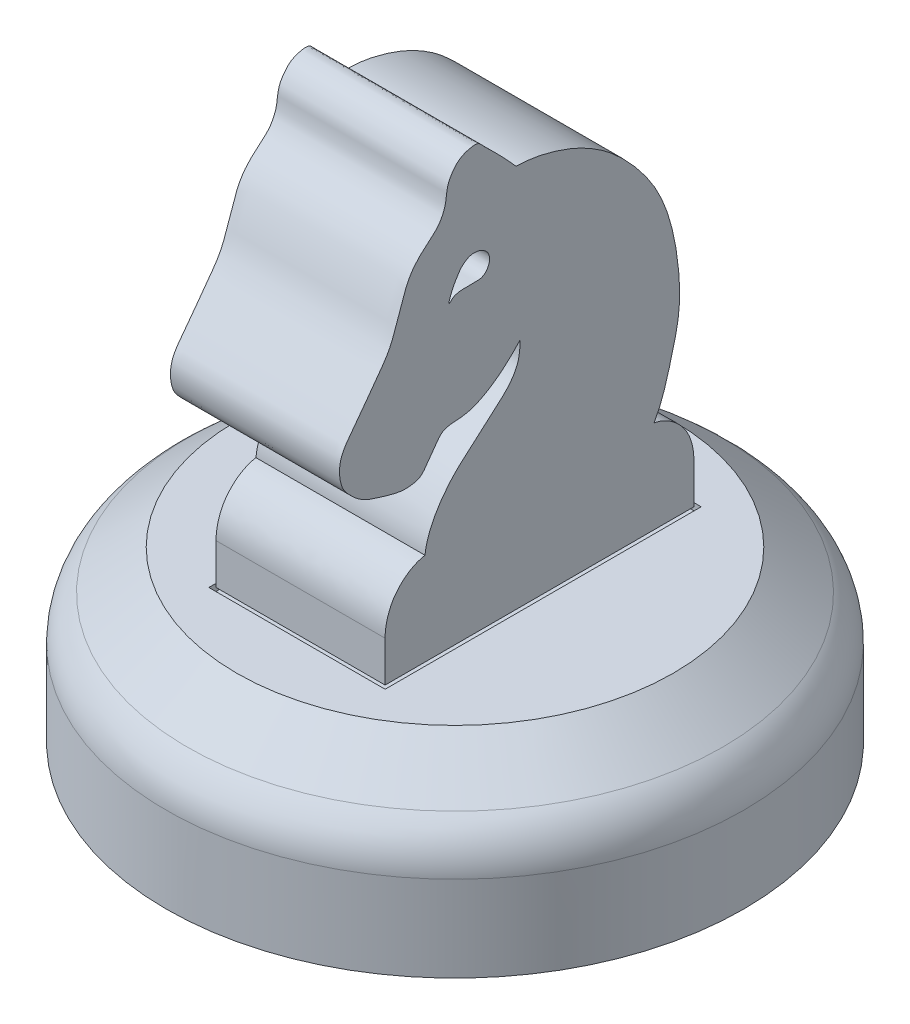
SolidWorks part; units mm, degrees
ref_plane "Front" through (0, 0, 0) normal (0, 0, 1) x (1, 0, 0)
ref_plane "Top" through (0, 0, 0) normal (0, 1, 0) x (1, 0, 0)
ref_plane "Right" through (0, 0, 0) normal (1, 0, 0) x (0, 0, -1)
sketch "Sketch1" plane through (0, 0, 0) normal (0, 1, 0) x (1, 0, 0)
  circle A0 centre (0, 0) radius 16.2719
  dimension "D1" = 32.5437
extrude "Boss-Extrude1" add sketch "Sketch1" along normal blind 6.35
sketch "Sketch2" plane through (0, 0, 0) normal (0, 0, 1) x (1, 0, 0)
  line L0 (-16.2719, 6.35) -> (-12.3031, 9.525)
  line L1 (-12.3031, 9.525) -> (0, 9.525)
  line L2 (0, 9.525) -> (0, 6.35)
  line L3 (16.2719, 6.35) -> (-16.2719, 6.35) construction
  line L4 (0, 6.35) -> (-16.2719, 6.35)
  line L5 (-16.2719, 0) -> (16.2719, 0) construction
  dimension "D1" = 3.9688
  dimension "D2" = 9.525
revolve "Revolve1" add sketch "Sketch2" angle 360 about L2
fillet "Fillet1" radius 3.175 1 edges at (0, 6.35, 16.2719)
sketch "Sketch3" plane through (0, 0, 0) normal (0, -1, 0) x (1, 0, 0)
  line L1 (-6.4516, -9.6266) -> (6.4516, -9.6266)
  line L2 (-6.4516, -9.6266) -> (-6.4516, 9.6266)
  line L3 (-6.4516, 9.6266) -> (6.4516, 9.6266)
  line L4 (6.4516, -9.6266) -> (6.4516, 9.6266)
  line L5 (-6.4516, -9.6266) -> (6.4516, 9.6266) construction
  line L6 (-6.4516, 9.6266) -> (6.4516, -9.6266) construction
  point P0 (0, 0)
  dimension "D1" = 19.2532
  dimension "D2" = 12.9032
extrude "Cut-Extrude1" cut sketch "Sketch3" against normal blind 4.7625
hole_wizard "#6 (0.204) Diameter Hole1" positions "Sketch4" profile "Sketch5" hole size "#6" standard "ANSI Inch" end condition through all
sketch "Sketch4" plane through (0, 4.7625, 0) normal (0, -1, 0) x (-1, 0, 0)
  point P0 (0, 0)
sketch "Sketch5" plane through (0, 4.7625, 0) normal (1, 0, 0) x (0, 0, -1)
  line L0 (0, 0) -> (0, 4.7625)
  line L1 (0, 4.7625) -> (2.5908, 4.7625)
  line L2 (2.5908, 4.7625) -> (2.5908, 0)
  line L5 (2.5908, 0) -> (0, 0)
  line L11 (0, -6.35) -> (0, 107.95) construction
  dimension "Thru Hole Dia." = 5.1816
  dimension "Thru Hole Depth" = 4.7625
sketch "Sketch6" plane through (0, 0, 0) normal (1, 0, 0) x (0, 0, -1)
  line L0 (27.0775, 134.8707) -> (197.7441, 134.8707) construction
  line L1 (-8.6995, 9.525) -> (8.6995, 9.525)
  line L2 (12.3031, 9.525) -> (-12.3031, 9.525) construction
  line L3 (-8.6995, 9.525) -> (-8.6995, 11.811)
  line L4 (8.6995, 9.525) -> (8.6995, 11.811)
  line L5 (0, 50) -> (0, -50) construction
  spline S0 degree 3 poles (-8.6995, 11.811) (-8.6995, 11.9816) (-8.6727, 12.3664) (-8.5285, 12.9065) (-8.2839, 13.452) (-7.7049, 14.2088) (-7.0216, 14.6403) (-6.4552, 14.738) knots 0 0 0 0 0.128234 0.288855 0.417857 0.575529 1 1 1 1
  spline S1 degree 3 poles (8.6995, 11.811) (8.6995, 11.9816) (8.6727, 12.3664) (8.5285, 12.9065) (8.2839, 13.452) (7.7049, 14.2088) (7.0216, 14.6403) (6.4552, 14.738) knots 0 0 0 0 0.128234 0.288855 0.417857 0.575529 1 1 1 1
  spline S2 degree 3 poles (-6.4552, 14.738) (-6.3837, 15.3671) (-5.8874, 16.6148) (-4.8428, 17.8972) (-3.6608, 18.894) (-2.7793, 19.6924) (-1.9404, 20.394) (-1.476, 20.9781) (-1.1264, 21.6496) (-1.0965, 22.2131) (-1.1061, 22.5542) knots 0 0 0 0 0.192258 0.405859 0.498919 0.666224 0.770848 0.83293 0.894029 1 1 1 1
  spline S3 degree 3 poles (-1.1061, 22.5542) (-1.5242, 22.0952) (-2.1576, 21.4895) (-3.0879, 20.8927) (-3.7545, 20.5659) (-4.4503, 20.4241) (-5.022, 20.4246) (-5.5073, 20.2864) (-5.774, 19.944) (-6.0312, 19.5889) (-6.2514, 19.2765) (-6.4472, 18.9785) (-6.6252, 18.7689) (-6.8431, 18.6203) (-7.2609, 18.5168) (-7.7407, 18.5081) (-8.389, 18.6533) (-8.998, 18.8259) (-9.7161, 19.0534) (-10.2835, 19.3937) (-10.7308, 19.8212) (-11.0742, 20.2218) (-11.2885, 20.899) (-11.3093, 21.8693) (-10.6701, 22.7146) (-9.9559, 23.6434) (-9.2777, 24.607) (-8.4729, 25.6576) (-8.0786, 26.7447) (-7.7533, 27.6784) (-7.492, 28.4592) (-7.135, 29.0694) (-6.6666, 29.5845) (-6.132, 30.0234) (-5.6961, 30.4121) (-5.4653, 30.8255) (-5.2831, 31.2653) (-5.2493, 31.7778) (-5.1337, 32.3233) (-4.8528, 32.7397) (-4.5619, 33.0715) (-4.2242, 33.2406) (-3.8597, 33.3461) (-3.4565, 33.3918) (-3.1826, 33.0719) (-2.8917, 32.7988) (-2.5209, 32.4196) (-2.1225, 32.0339) (-1.7195, 31.5916) (-1.4573, 31.302) (-1.3179, 31.1488) knots 0 0 0 0 0.060185 0.083944 0.106743 0.131602 0.1517 0.162138 0.178974 0.191699 0.205012 0.215804 0.226254 0.231332 0.241037 0.267259 0.276935 0.305212 0.328527 0.349561 0.368397 0.388495 0.399373 0.436694 0.476526 0.498153 0.550637 0.590476 0.625187 0.661565 0.686424 0.704516 0.729532 0.753201 0.771645 0.785337 0.798629 0.817299 0.834698 0.851765 0.865242 0.876941 0.887382 0.902945 0.911138 0.926285 0.942165 0.962199 0.979971 1 1 1 1
  spline S4 degree 3 poles (-1.3179, 31.1488) (-0.6314, 31.1431) (0.615, 30.9171) (2.4211, 30.2419) (4.0211, 29.2202) (5.3792, 27.8375) (6.4189, 26.4437) (7.1156, 24.9863) (7.5672, 23.4519) (7.8665, 21.5773) (7.966, 19.4481) (7.3408, 17.1101) (6.9073, 15.5348) (6.4552, 14.738) knots 0 0 0 0 0.095317 0.175052 0.26721 0.356914 0.443609 0.508026 0.58072 0.665407 0.772328 0.873993 1 1 1 1
  spline S5 degree 3 poles (-4.9557, 26.8493) (-5.2053, 26.1749) (-4.9327, 26.4831) (-4.7483, 26.584) (-4.4297, 26.6629) (-4.024, 26.6413) (-3.634, 26.6461) (-3.3228, 26.6568) (-3.0869, 26.7717) (-2.9358, 26.9604) (-2.8267, 27.1671) (-2.8011, 27.4116) (-2.8531, 27.6538) (-3.0007, 27.8429) (-3.1768, 27.9888) (-3.3995, 28.079) (-3.6513, 28.1165) (-3.9441, 28.0897) (-4.211, 27.9338) (-4.445, 27.7279) (-4.6185, 27.46) (-4.8162, 27.1346) (-4.9557, 26.8493) (-5.2053, 26.1749) (-4.9327, 26.4831) knots -0.192918 -0.136375 -0.071516 0 0.037676 0.055516 0.103904 0.18431 0.245368 0.285825 0.328299 0.362295 0.397084 0.435792 0.474404 0.509262 0.545392 0.579954 0.61966 0.663362 0.713893 0.760702 0.807082 0.863625 0.928484 1 1.037676 1.055516 1.103904 only from (-5.0862, 26.3389) to (-5.0862, 26.3389)
  point P6 (0, 9.525)
  dimension "D1" = 17.399
  dimension "D2" = 2.286
extrude "Boss-Extrude2" add sketch "Sketch6" along normal mid plane 9.525 separate body
sketch "Sketch7" plane through (0, 9.525, 0) normal (0, 1, 0) x (1, 0, 0)
  line L14 (-4.9657, -8.9027) -> (4.9657, -8.9027)
  line L15 (-4.9657, 8.9027) -> (-4.9657, -8.9027)
  line L16 (4.9657, 8.9027) -> (-4.9657, 8.9027)
  line L17 (4.9657, -8.9027) -> (4.9657, 8.9027)
  line L18 (-4.9657, -8.9027) -> (4.9657, -8.9027)
  line L19 (-4.9657, 8.9027) -> (-4.9657, -8.9027)
  line L20 (4.9657, 8.9027) -> (-4.9657, 8.9027)
  line L21 (4.9657, -8.9027) -> (4.9657, 8.9027)
  dimension "D1" = 0.2032
extrude "Cut-Extrude2" cut sketch "Sketch7" against normal blind 0.3969
